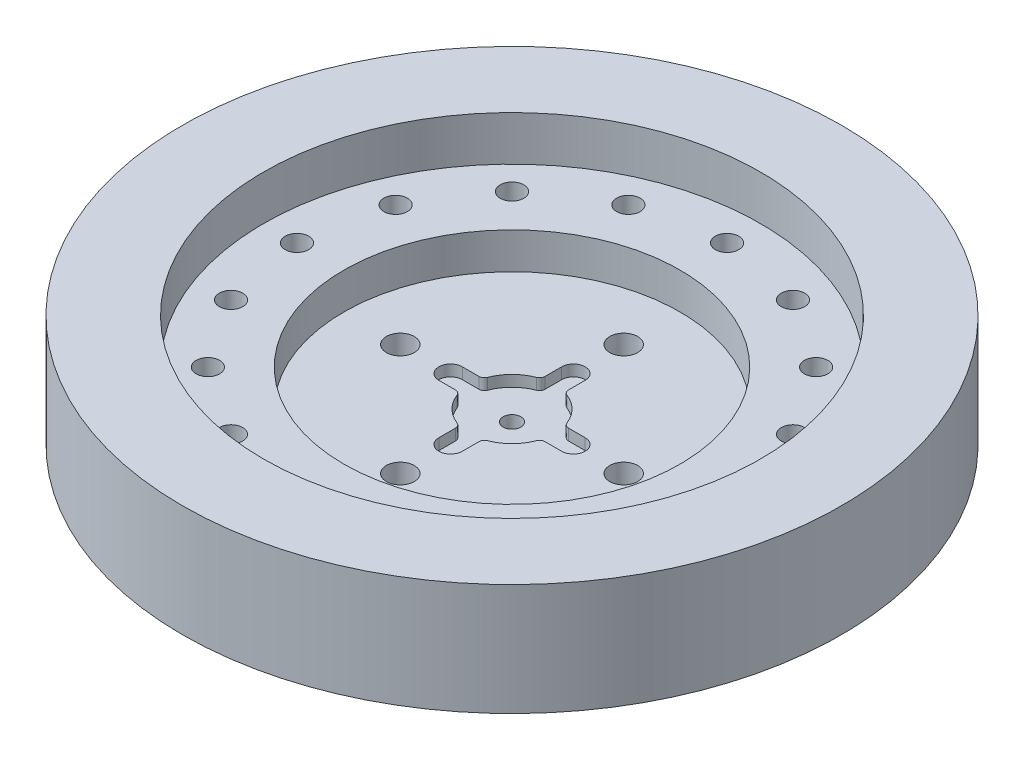
SolidWorks part; units mm, degrees
ref_plane "Front Plane" through (0, 0, 0) normal (0, 0, 1) x (1, 0, 0)
ref_plane "Top Plane" through (0, 0, 0) normal (0, 1, 0) x (1, 0, 0)
ref_plane "Right Plane" through (0, 0, 0) normal (1, 0, 0) x (0, 0, -1)
other "Configuration Table"
sketch "草图1" plane through (0, 0, 0) normal (0, 1, 0) x (1, 0, 0)
  circle A0 centre (0, 0) radius 59
  dimension "D1" = 118
extrude "凸台-拉伸1" add sketch "草图1" along normal blind 20
sketch "草图2" plane through (0, 20, 0) normal (0, 1, 0) x (1, 0, 0)
  circle A0 centre (0, 0) radius 44.5
  dimension "D1" = 89
extrude "切除-拉伸1" cut sketch "草图2" against normal blind 8
sketch "草图3" plane through (0, 12, 0) normal (0, 1, 0) x (1, 0, 0)
  circle A0 centre (0, 0) radius 30.1
  dimension "D1" = 60.2
extrude "切除-拉伸2" cut sketch "草图3" against normal blind 6.5
sketch "草图4" plane through (0, 0, 0) normal (0, -1, 0) x (1, 0, 0)
  line L0 (0, 0) -> (0, 38.5) construction
  circle A0 centre (0, 38.5) radius 2.1
  circle A1 centre (14.7333, 35.5694) radius 2.1
  circle A2 centre (27.2236, 27.2236) radius 2.1
  circle A3 centre (35.5694, 14.7333) radius 2.1
  circle A4 centre (38.5, 0) radius 2.1
  circle A5 centre (35.5694, -14.7333) radius 2.1
  circle A6 centre (27.2236, -27.2236) radius 2.1
  circle A7 centre (14.7333, -35.5694) radius 2.1
  circle A8 centre (0, -38.5) radius 2.1
  circle A9 centre (-14.7333, -35.5694) radius 2.1
  circle A10 centre (-27.2236, -27.2236) radius 2.1
  circle A11 centre (-35.5694, -14.7333) radius 2.1
  circle A12 centre (-38.5, 0) radius 2.1
  circle A13 centre (-35.5694, 14.7333) radius 2.1
  circle A14 centre (-27.2236, 27.2236) radius 2.1
  circle A15 centre (-14.7333, 35.5694) radius 2.1
  point P20 (0, 0)
  dimension "D1" = 16
extrude "切除-拉伸3" cut sketch "草图4" against normal through all
sketch "草图5" plane through (0, 0, 0) normal (0, -1, 0) x (1, 0, 0)
  line L0 (0, 0) -> (0, 38.5) construction
  circle A0 centre (0, 38.5) radius 3.75
  circle A1 centre (14.7333, 35.5694) radius 3.75
  circle A2 centre (27.2236, 27.2236) radius 3.75
  circle A3 centre (35.5694, 14.7333) radius 3.75
  circle A4 centre (38.5, 0) radius 3.75
  circle A5 centre (35.5694, -14.7333) radius 3.75
  circle A6 centre (27.2236, -27.2236) radius 3.75
  circle A7 centre (14.7333, -35.5694) radius 3.75
  circle A8 centre (0, -38.5) radius 3.75
  circle A9 centre (-14.7333, -35.5694) radius 3.75
  circle A10 centre (-27.2236, -27.2236) radius 3.75
  circle A11 centre (-35.5694, -14.7333) radius 3.75
  circle A12 centre (-38.5, 0) radius 3.75
  circle A13 centre (-35.5694, 14.7333) radius 3.75
  circle A14 centre (-27.2236, 27.2236) radius 3.75
  circle A15 centre (-14.7333, 35.5694) radius 3.75
  point P21 (0, 0)
  dimension "D1" = 16
extrude "切除-拉伸4" cut sketch "草图5" against normal blind 5
sketch "草图11" plane through (0, 0, 0) normal (0, -1, 0) x (1, 0, 0)
  line L0 (0, 0) -> (0, 20) construction
  line L1 (0, 0) -> (0, -20) construction
  line L2 (0, 0) -> (20, 0) construction
  line L3 (0, 0) -> (-20, 0) construction
sketch "草图14" plane through (0, 0, 0) normal (0, -1, 0) x (-1, 0, 0)
  point P0 (0, 20)
  point P3 (-20, 0)
  point P6 (0, -20)
  point P9 (20, 0)
hole_wizard "M6x1.0 螺纹孔2" positions "草图14" profile "草图13" tap size "M6x1.0" standard "ANSI Metric" end condition through all
sketch "草图13" plane through (0, 0, -20) normal (1, 0, 0) x (0, 0, -1)
  line L0 (0, 0) -> (0, 20)
  line L1 (0, 20) -> (2.5, 20)
  line L2 (2.5, 20) -> (2.5, 0)
  line L5 (2.5, 0) -> (0, 0)
  line L11 (0, -6.35) -> (0, 107.95) construction
  dimension "通孔螺纹孔钻头直径" = 5
  dimension "通孔螺纹孔钻头深度" = 20
cosmetic thread "孔螺纹线2" parameters "D2"=6
cosmetic thread "孔螺纹线3" parameters "D2"=6
cosmetic thread "孔螺纹线4" parameters "D2"=6
cosmetic thread "孔螺纹线5" parameters "D2"=6
sketch "草图17" plane through (0, 20, 0) normal (0, 1, 0) x (1, 0, 0)
  line L0 (-20, 0) -> (20, 0) construction
  line L1 (0, 0) -> (0, -59) construction
  line L2 (0, -59) -> (0, -58.5) construction
  line L11 (-1, -59) -> (-1, -58.5)
  line L12 (1, -59) -> (1, -58.5)
  line L13 (0, 59) -> (0, 58.5) construction
  line L14 (-1, 59) -> (-1, 58.5)
  line L15 (1, 59) -> (1, 58.5)
  circle A0 centre (0, 0) radius 59 construction
  arc A1 (-1, -59) -> (1, -59) centre (0, -59) ccw
  arc A2 (1, -58.5) -> (-1, -58.5) centre (0, -58.5) ccw
  arc A3 (-1, 59) -> (1, 59) centre (0, 59) cw
  arc A4 (1, 58.5) -> (-1, 58.5) centre (0, 58.5) cw
  point P8 (0, -58.75)
  point P11 (0, -58)
  point P19 (0, 58.75)
extrude "切除-拉伸7" [suppressed] cut sketch "草图17" against normal blind 1 contours A1
sketch "草图26" plane through (0, 0, 0) normal (0, -1, 0) x (1, 0, 0)
  circle A0 centre (0, 0) radius 3.1
extrude "切除-拉伸14" cut sketch "草图26" against normal blind 1.2
sketch "草图28" plane through (0, 5.5, 0) normal (0, 1, 0) x (1, 0, 0)
  line L0 (0, 0) -> (0, 7.6) construction
  line L1 (0, 5) -> (0, 11) construction
  line L10 (0, 0) -> (0, 20) construction
  line L11 (-2.1, 5) -> (-2.1, 11)
  line L12 (2.1, 5) -> (2.1, 11)
  line L13 (5, 0) -> (11, 0) construction
  line L14 (5, 2.1) -> (11, 2.1)
  line L15 (5, -2.1) -> (11, -2.1)
  line L16 (0, -5) -> (0, -11) construction
  line L17 (2.1, -5) -> (2.1, -11)
  line L18 (-2.1, -5) -> (-2.1, -11)
  line L19 (-5, 0) -> (-11, 0) construction
  line L20 (-5, -2.1) -> (-11, -2.1)
  line L21 (-5, 2.1) -> (-11, 2.1)
  circle A9 centre (0, 0) radius 7.6
  arc A10 (-2.1, 5) -> (2.1, 5) centre (0, 5) ccw
  arc A11 (2.1, 11) -> (-2.1, 11) centre (0, 11) ccw
  arc A12 (5, 2.1) -> (5, -2.1) centre (5, 0) ccw
  arc A13 (11, -2.1) -> (11, 2.1) centre (11, 0) ccw
  arc A14 (2.1, -5) -> (-2.1, -5) centre (0, -5) ccw
  arc A15 (-2.1, -11) -> (2.1, -11) centre (0, -11) ccw
  arc A16 (-5, -2.1) -> (-5, 2.1) centre (-5, 0) ccw
  arc A17 (-11, 2.1) -> (-11, -2.1) centre (-11, 0) ccw
  point P7 (0, 8)
  point P17 (8, 0)
  point P24 (0, -8)
  point P32 (-8, 0)
  point P37 (0, 0)
  dimension "D1" = 6
  dimension "D2" = 5
extrude "切除-拉伸17" cut sketch "草图28" against normal blind 2 contours L12 A11 L11 A9 | A16 L20 A9 L18 A14 L17 L15 A12 L14 L12 A10 L11 L21 | L21 A17 L20 A9 | L18 A15 L17 A9 | L15 A13 L14 A9 | L11 A10 L12 A9 | L20 A16 L21 A9 | L14 A12 L15 A9 | L17 A14 L18 A9
fillet "圆角1" radius 1 8 edges at (7.3041, 4.5, -2.1) (7.3041, 4.5, 2.1) (2.1, 4.5, 7.3041) (-2.1, 4.5, 7.3041) (-7.3041, 4.5, 2.1) (2.1, 4.5, -7.3041) (-7.3041, 4.5, -2.1) (-2.1, 4.5, -7.3041)
sketch "草图29" plane through (0, 1.2, 0) normal (0, -1, 0) x (1, 0, 0)
  circle A0 centre (0, 0) radius 1.6
extrude "切除-拉伸18" cut sketch "草图29" against normal through all
